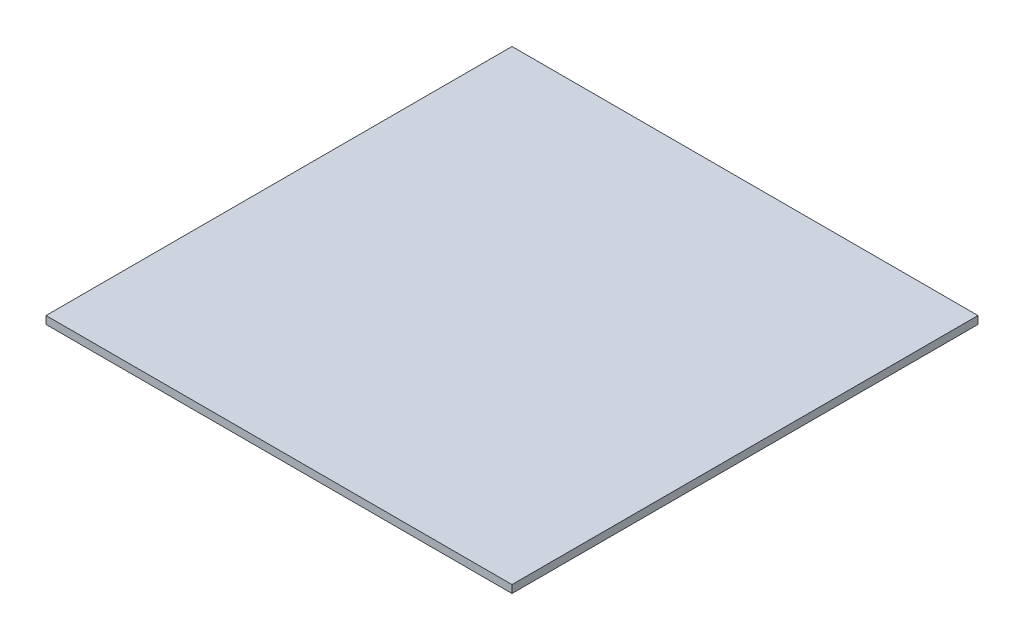
SolidWorks part; units mm, degrees
ref_plane "前视基准面" through (0, 0, 0) normal (0, 0, 1) x (1, 0, 0)
ref_plane "上视基准面" through (0, 0, 0) normal (0, 1, 0) x (1, 0, 0)
ref_plane "右视基准面" through (0, 0, 0) normal (1, 0, 0) x (0, 0, -1)
sketch "草图1" plane through (0, 0, 0) normal (0, 1, 0) x (1, 0, 0)
  line L1 (-150, 150) -> (150, 150)
  line L2 (-150, 150) -> (-150, -150)
  line L3 (-150, -150) -> (150, -150)
  line L4 (150, 150) -> (150, -150)
  line L5 (-150, 150) -> (150, -150) construction
  line L6 (-150, -150) -> (150, 150) construction
  point P0 (0, 0)
  dimension "D1" = 300
  dimension "D2" = 300
extrude "凸台-拉伸1" add sketch "草图1" along normal blind 5
